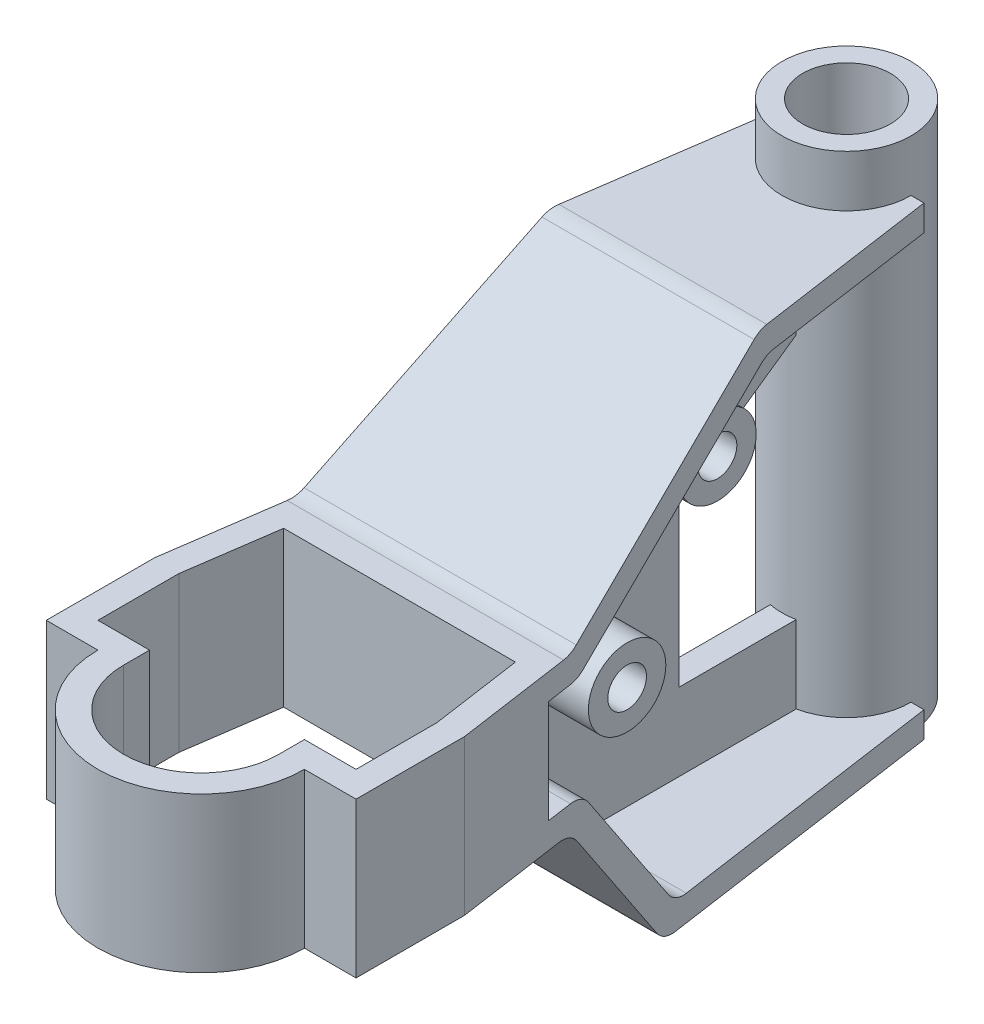
SolidWorks part; units mm, degrees
other "Markup1"
sketch "Sketch10" plane through (60, 140, 40) normal (0.6884, 0.3493, 0.6357) x (0.6614, 0.0575, -0.7479)
material "1060 Alloy"
ref_plane "Front Plane" through (0, 0, 0) normal (0, 0, 1) x (1, 0, 0)
ref_plane "Top Plane" through (0, 0, 0) normal (0, 1, 0) x (1, 0, 0)
ref_plane "Right Plane" through (0, 0, 0) normal (1, 0, 0) x (0, 0, -1)
sketch "Sketch1" plane through (0, 0, 0) normal (1, 0, 0) x (0, 0, -1)
  line L0 (0, 0) -> (0, 60)
  line L1 (0, 60) -> (90, 60)
  line L2 (90, 60) -> (175.6889, 120)
  line L3 (175.6889, 120) -> (250, 120)
  line L4 (250, 120) -> (250, 92.6829)
  line L5 (250, 92.6829) -> (180, 43.6683)
  line L6 (180, 43.6683) -> (180, -20)
  line L7 (180, -20) -> (250, -20)
  line L8 (250, -20) -> (250, -60)
  line L9 (250, -60) -> (132.0125, -60)
  line L10 (132.0125, -60) -> (90, 0)
  line L11 (90, 0) -> (0, 0)
  line L12 (250, 92.6829) -> (250, -20) construction
  line L13 (90, 60) -> (90, 0) construction
  dimension "D1" = 60
  dimension "D2" = 90
  dimension "D3" = 145
  dimension "D5" = 65
  dimension "D6" = 40
  dimension "D7" = 70
  dimension "D8" = 60
  dimension "D9" = 250
  dimension "D4" = 180
extrude "Boss-Extrude1" add sketch "Sketch1" along normal blind 60
sketch "Sketch2" plane through (0, 120, 0) normal (0, 1, 0) x (1, 0, 0)
  line L0 (60, 42.0348) -> (30, 250)
  line L1 (60, 90) -> (60, 0) construction
  line L2 (60, 250) -> (0, 250) construction
  line L3 (30, 250) -> (60, 250)
  line L4 (60, 250) -> (60, 42.0348)
extrude "Cut-Extrude1" cut sketch "Sketch2" against normal through all
sketch "Sketch4" plane through (0, 0, 0) normal (1, 0, 0) x (0, 0, -1)
  line L0 (80, 50) -> (80, 10)
  line L8 (250, -50) -> (137.2181, -50)
  line L9 (137.2181, -50) -> (95.2057, 10)
  line L10 (95.2057, 10) -> (42.0348, 10)
  line L11 (250, -50) -> (137.2181, -50)
  line L12 (137.2181, -50) -> (95.2057, 10)
  line L13 (95.2057, 10) -> (80, 10)
  line L14 (0, 60) -> (0, 0) construction
  line L15 (250, 110) -> (250, -50)
  line L17 (178.8419, 110) -> (250, 110)
  line L18 (93.153, 50) -> (178.8419, 110)
  line L19 (42.0348, 50) -> (93.153, 50)
  line L20 (178.8419, 110) -> (250, 110)
  line L21 (93.153, 50) -> (178.8419, 110)
  line L22 (80, 50) -> (93.153, 50)
  dimension "D3" = 80
  dimension "D1" = 10
  dimension "D2" = 10
extrude "Cut-Extrude2" cut sketch "Sketch4" along normal up to next from offset 5
fillet "Fillet1" radius 10 8 edges at (20.3599, 120, -175.6889) (26.5404, 60, -90) (22.6325, 110, -178.8419) (28.813, 50, -93.153) (23.5101, -60, -132.0125) (26.5404, 0, -90) (25.6347, -50, -137.2181) (28.6649, 10, -95.2057)
sketch "Sketch8" plane through (0, 60, 0) normal (0, 1, 0) x (1, 0, 0)
  line L0 (0, 0) -> (0, -40)
  line L1 (0, 0) -> (40, 0)
  arc A0 (0, -40) -> (40, 0) centre (0, 0) ccw
  dimension "D1" = 40
extrude "Boss-Extrude4" add sketch "Sketch8" against normal up to surface (60 mm away) up to face at (34.7663, 0, -42.3247)
sketch "Sketch3" plane through (0, -60, 0) normal (0, -1, 0) x (1, 0, 0)
  line L0 (0, -275) -> (0, -225)
  arc A0 (0, -275) -> (0, -225) centre (0, -250) ccw
  dimension "D1" = 50
extrude "Boss-Extrude2" add sketch "Sketch3" against normal blind 200
sketch "Sketch5" plane through (0, 60, 0) normal (0, 1, 0) x (1, 0, 0)
  line L0 (40, 10) -> (30, 10)
  line L1 (30, 10) -> (30, 0)
  line L2 (0, 76.847) -> (0, -30)
  line L13 (40, 10) -> (50, 10)
  line L14 (50, 10) -> (50, 41.3172)
  line L20 (50, 41.3172) -> (44.8747, 76.847)
  line L21 (44.8747, 76.847) -> (0, 76.847)
  line L22 (40, 10) -> (50, 10)
  line L23 (50, 10) -> (50, 41.3172)
  line L24 (50, 41.3172) -> (44.8747, 76.847)
  line L25 (44.8747, 76.847) -> (0, 76.847)
  circle A0 centre (0, 250) radius 17
  arc A1 (0, 225) -> (0, 275) centre (0, 250) ccw construction
  arc A4 (0, -30) -> (30, 0) centre (0, 0) ccw
  arc A5 (0, -30) -> (30, 0) centre (0, 0) ccw
  dimension "D2" = 8
  dimension "D1" = 10
  dimension "D3" = 10
extrude "Cut-Extrude3" cut sketch "Sketch5" against normal through all both and the other way through all
sketch "Sketch6" plane through (5, 0, 0) normal (1, 0, 0) x (0, 0, -1)
  line L0 (0, 60) -> (0, 0) construction
  line L1 (0, 0) -> (42.0348, 0) construction
  circle A0 centre (175, 70) radius 15
  circle A1 centre (140, 10) radius 15
  dimension "D1" = 140
  dimension "D2" = 175
  dimension "D5" = 30
  dimension "D3" = 70
  dimension "D4" = 10
extrude "Boss-Extrude3" add sketch "Sketch6" along normal blind 20
sketch "Sketch7" plane through (25, 0, 0) normal (1, 0, 0) x (0, 0, -1)
  circle A0 centre (140, 10) radius 7.5
  circle A1 centre (175, 70) radius 7.5
  dimension "D1" = 15
extrude "Cut-Extrude4" cut sketch "Sketch7" against normal up to next
mirror "Mirror2" about plane through (0, 0, 0) normal (-1, 0, 0) of bodies 108
equation "\"A\"= 60"
equation "\"B\"= 60"
equation "\"C\"= 100"
equation "\"D\"= 100"
equation "\"E\"= 100"
equation "\"X\"= \"A\" / 5"
equation "\"Y\"= \"C\" + 10"
equation "\"D1@Sketch1\"=\"A\""
equation "\"D4@Sketch1\"=\"A\" * 3"
equation "\"D1@Boss-Extrude1\"=\"B\""
equation "\"D1@Boss-Extrude2\"= \"A\" * 3 + 20"
